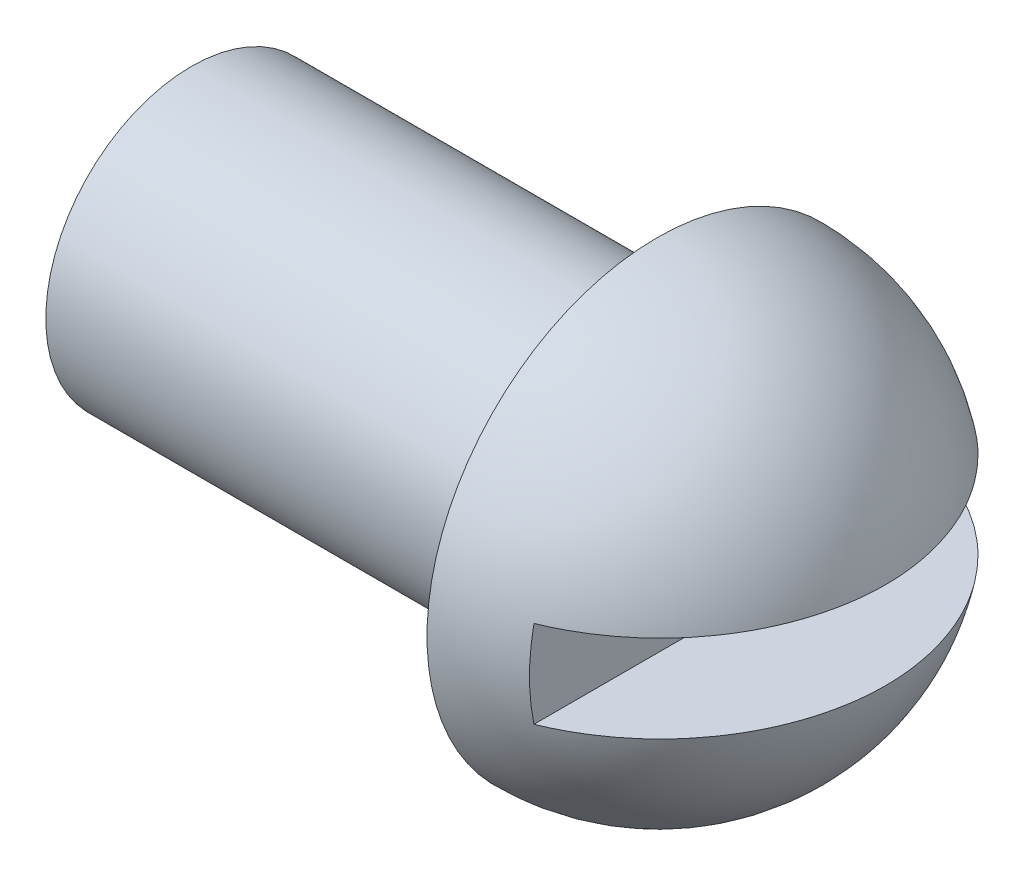
SolidWorks part; units mm, degrees
ref_plane "Plano frontal" through (0, 0, 0) normal (0, 0, 1) x (1, 0, 0)
ref_plane "Plano superior" through (0, 0, 0) normal (0, 1, 0) x (1, 0, 0)
ref_plane "Plano direito" through (0, 0, 0) normal (1, 0, 0) x (0, 0, -1)
sketch "Esboço1" plane through (0, 0, 0) normal (0, 0, 1) x (1, 0, 0)
  line L0 (0, 0) -> (0, 2.5)
  line L1 (0, 2.5) -> (8, 2.5)
  line L2 (8, 3.9537) -> (8, 2.5)
  line L3 (12, 0) -> (0, 0)
  arc A0 (12, 0) -> (8, 3.9537) centre (8.0003, -0.0463) ccw
  dimension "D1" = 8
  dimension "D5" = 4
  dimension "D2" = 12
  dimension "D3" = 2.5
revolve "Revolução1" add sketch "Esboço1" angle 360 about L3
cosmetic thread "Representação de rosca1" parameters "D2"=4.11
sketch "Esboço2" plane through (0, 0, 0) normal (0, 0, 1) x (1, 0, 0)
  line L0 (0, 0) -> (12.6471, 0)
  line L2 (12.6471, -0.75) -> (9.4767, -0.75)
  line L3 (12.6471, -0.75) -> (12.6471, 0.75)
  line L4 (12.6471, 0.75) -> (9.4767, 0.75)
  line L5 (9.4767, -0.75) -> (9.4767, 0.75)
  point P7 (11.9918, 0.0107)
  point P8 (12, 0)
  point P10 (11.9874, 0.0196)
  point P12 (12.6471, 0)
  dimension "D1" = 1.5
extrude "Corte-extrusão1" cut sketch "Esboço2" against normal through all both and the other way through all contours L4 L5 L2 L3
